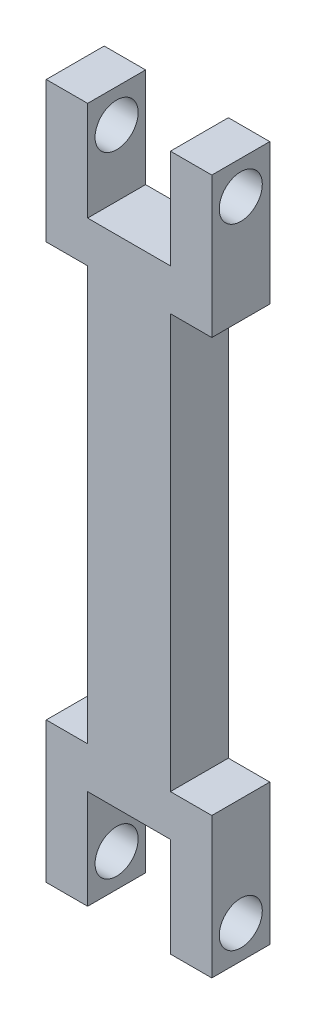
SolidWorks part; units mm, degrees
ref_plane "Front Plane" through (0, 0, 0) normal (0, 0, 1) x (1, 0, 0)
ref_plane "Top Plane" through (0, 0, 0) normal (0, 1, 0) x (1, 0, 0)
ref_plane "Right Plane" through (0, 0, 0) normal (1, 0, 0) x (0, 0, -1)
sketch "Sketch1" plane through (0, 0, 0) normal (0, 1, 0) x (1, 0, 0)
  line L1 (0, 0) -> (12.7, 0)
  line L2 (0, 0) -> (0, 8.89)
  line L3 (0, 8.89) -> (12.7, 8.89)
  line L4 (12.7, 0) -> (12.7, 8.89)
extrude "Boss-Extrude1" add sketch "Sketch1" along normal blind 76.2
sketch "Sketch2" plane through (12.7, 0, 0) normal (1, 0, 0) x (0, 0, -1)
  line L4 (0, 0) -> (8.89, 0)
  line L5 (0, 0) -> (0, 6.35)
  line L6 (8.89, 0) -> (8.89, 6.35)
  line L7 (0, 6.35) -> (8.89, 6.35)
  line L9 (0, 76.2) -> (8.89, 76.2)
  line L10 (0, 76.2) -> (0, 69.85)
  line L11 (8.89, 76.2) -> (8.89, 69.85)
  line L12 (0, 69.85) -> (8.89, 69.85)
extrude "Boss-Extrude2" add sketch "Sketch2" along normal blind 6.35
sketch "Sketch3" plane through (0, 0, 0) normal (-1, 0, 0) x (0, 0, 1)
  line L4 (-8.89, 0) -> (0, 0)
  line L5 (-8.89, 0) -> (-8.89, 6.35)
  line L6 (0, 0) -> (0, 6.35)
  line L7 (-8.89, 6.35) -> (0, 6.35)
  line L8 (-8.89, 76.2) -> (0, 76.2)
  line L9 (-8.89, 76.2) -> (-8.89, 69.85)
  line L10 (0, 76.2) -> (0, 69.85)
  line L11 (-8.89, 69.85) -> (0, 69.85)
extrude "Boss-Extrude3" add sketch "Sketch3" along normal blind 6.35
sketch "Sketch4" plane through (0, 76.2, 0) normal (0, 1, 0) x (1, 0, 0)
  line L8 (-6.35, 8.89) -> (-6.35, 0)
  line L9 (-6.35, 8.89) -> (0, 8.89)
  line L10 (-6.35, 0) -> (0, 0)
  line L11 (0, 8.89) -> (0, 0)
  line L12 (19.05, 8.89) -> (19.05, 0)
  line L13 (19.05, 8.89) -> (12.7, 8.89)
  line L14 (19.05, 0) -> (12.7, 0)
  line L15 (12.7, 8.89) -> (12.7, 0)
extrude "Boss-Extrude4" add sketch "Sketch4" along normal blind 15.24
sketch "Sketch6" plane through (19.05, 0, 0) normal (1, 0, 0) x (0, 0, -1)
  line L0 (4.445, 91.44) -> (4.445, 86.36) construction
  line L1 (0, 91.44) -> (8.89, 91.44) construction
  circle A1 centre (4.445, 86.36) radius 3.302
sketch "Sketch7" plane through (0, 0, 0) normal (0, -1, 0) x (1, 0, 0)
  line L0 (-6.35, 0) -> (-6.35, -8.89)
  line L1 (-6.35, 0) -> (0, 0)
  line L2 (-6.35, -8.89) -> (0, -8.89)
  line L3 (0, 0) -> (0, -8.89)
  line L4 (19.05, 0) -> (19.05, -8.89)
  line L5 (19.05, 0) -> (12.7, 0)
  line L6 (19.05, -8.89) -> (12.7, -8.89)
  line L7 (12.7, 0) -> (12.7, -8.89)
extrude "Boss-Extrude5" add sketch "Sketch7" along normal blind 15.24
sketch "Sketch8" plane through (19.05, 0, 0) normal (1, 0, 0) x (0, 0, -1)
  line L0 (4.445, -15.24) -> (4.445, -10.16) construction
  line L1 (8.89, -15.24) -> (0, -15.24) construction
  circle A0 centre (4.445, -10.16) radius 3.302
extrude "Cut-Extrude2" cut sketch "Sketch8" against normal blind 35.306
extrude "Cut-Extrude3" cut sketch "Sketch6" against normal blind 33.528
